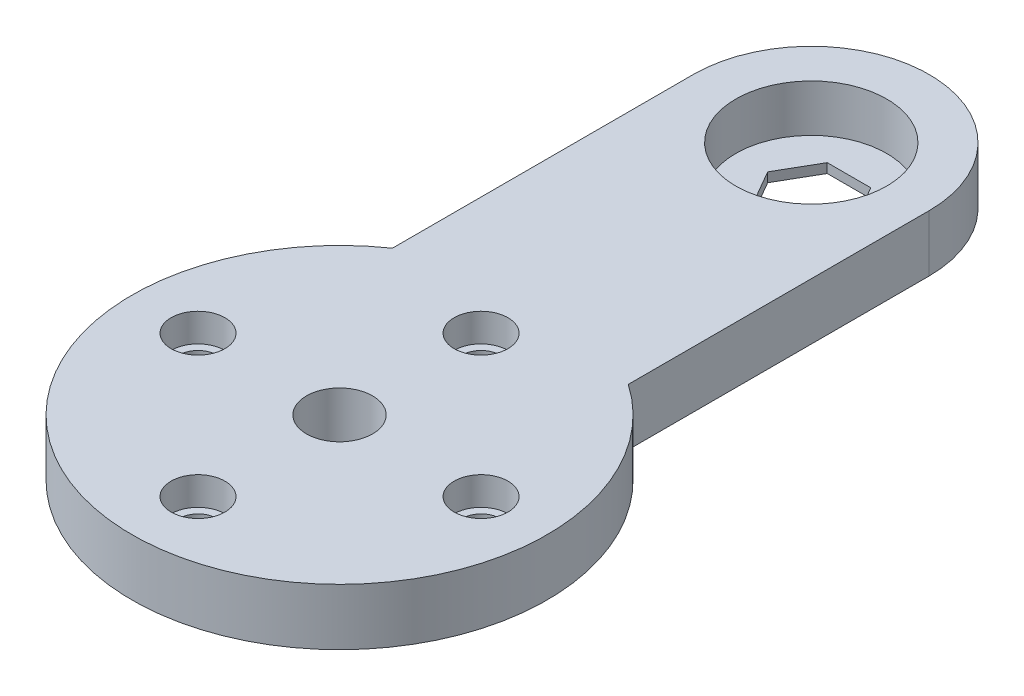
SolidWorks part; units mm, degrees
ref_plane "Front Plane" through (0, 0, 0) normal (0, 0, 1) x (1, 0, 0)
ref_plane "Top Plane" through (0, 0, 0) normal (0, 1, 0) x (1, 0, 0)
ref_plane "Right Plane" through (0, 0, 0) normal (1, 0, 0) x (0, 0, -1)
sketch "Sketch1" plane through (0, 0, 0) normal (0, 1, 0) x (1, 0, 0)
  line L0 (0, 0) -> (-21084.7986, 0) construction
  line L1 (0, 0) -> (0, -21084.7986) construction
  line L4 (-12.5, 0) -> (-12.5, -31.8961)
  line L5 (12.5, 0) -> (12.5, -31.8961)
  arc A0 (12.5, 0) -> (-12.5, 0) centre (0, 0) ccw
  arc A2 (-12.5, -31.8961) -> (12.5, -31.8961) centre (0, -50) ccw
  dimension "D1" = 25
  dimension "D2" = 44
  dimension "D3" = 50
extrude "Boss-Extrude1" add sketch "Sketch1" along normal blind 6
sketch "Sketch2" plane through (0, 6, 0) normal (0, 1, 0) x (1, 0, 0)
  line L0 (0, 0) -> (-50000, 0) construction
  line L1 (0, 0) -> (0, -50000) construction
  circle A0 centre (0, -50) radius 15 construction
  circle A1 centre (0, -35) radius 2.85
  circle A2 centre (15, -50) radius 2.85
  circle A3 centre (0, -65) radius 2.85
  circle A4 centre (-15, -50) radius 2.85
  point P19 (0, -50)
  dimension "D1" = 30
  dimension "D2" = 5.7
extrude "Cut-Extrude1" cut sketch "Sketch2" against normal blind 3
sketch "Sketch3" plane through (0, 6, 0) normal (0, 1, 0) x (1, 0, 0)
  line L0 (0, 0) -> (-50000, 0) construction
  line L1 (0, 0) -> (0, -50000) construction
  line L2 (-15, -50) -> (49985, -50) construction
  circle A0 centre (0, -35) radius 2
  circle A1 centre (15, -50) radius 2
  circle A2 centre (0, -65) radius 2
  circle A3 centre (-15, -50) radius 2
  circle A4 centre (0, -50) radius 3.5
  point P12 (0, -50)
  dimension "D1" = 4
  dimension "D2" = 7
extrude "Cut-Extrude2" cut sketch "Sketch3" against normal through all
sketch "Sketch4" plane through (0, 6, 0) normal (0, 1, 0) x (1, 0, 0)
  line L0 (0, 0) -> (-50000, 0) construction
  line L1 (0, 0) -> (0, -50000) construction
  circle A0 centre (0, 0) radius 8
  dimension "D1" = 16
extrude "Cut-Extrude3" cut sketch "Sketch4" against normal blind 5 contours A0
sketch "Sketch5" plane through (0, 6, 0) normal (0, 1, 0) x (1, 0, 0)
  circle A0 centre (0, 0) radius 3.5
  dimension "D1" = 7
extrude "Cut-Extrude4" cut sketch "Sketch5" against normal through all
sketch "Sketch6" plane through (0, 0, 0) normal (0, -1, 0) x (1, 0, 0)
  line L1 (4.6188, 0) -> (2.3094, 4)
  line L2 (2.3094, 4) -> (-2.3094, 4)
  line L3 (-2.3094, 4) -> (-4.6188, 0)
  line L4 (-4.6188, 0) -> (-2.3094, -4)
  line L5 (-2.3094, -4) -> (2.3094, -4)
  line L6 (2.3094, -4) -> (4.6188, 0)
  circle A0 centre (0, 0) radius 4 construction
  dimension "D1" = 8
extrude "Cut-Extrude5" cut sketch "Sketch6" against normal blind 3
